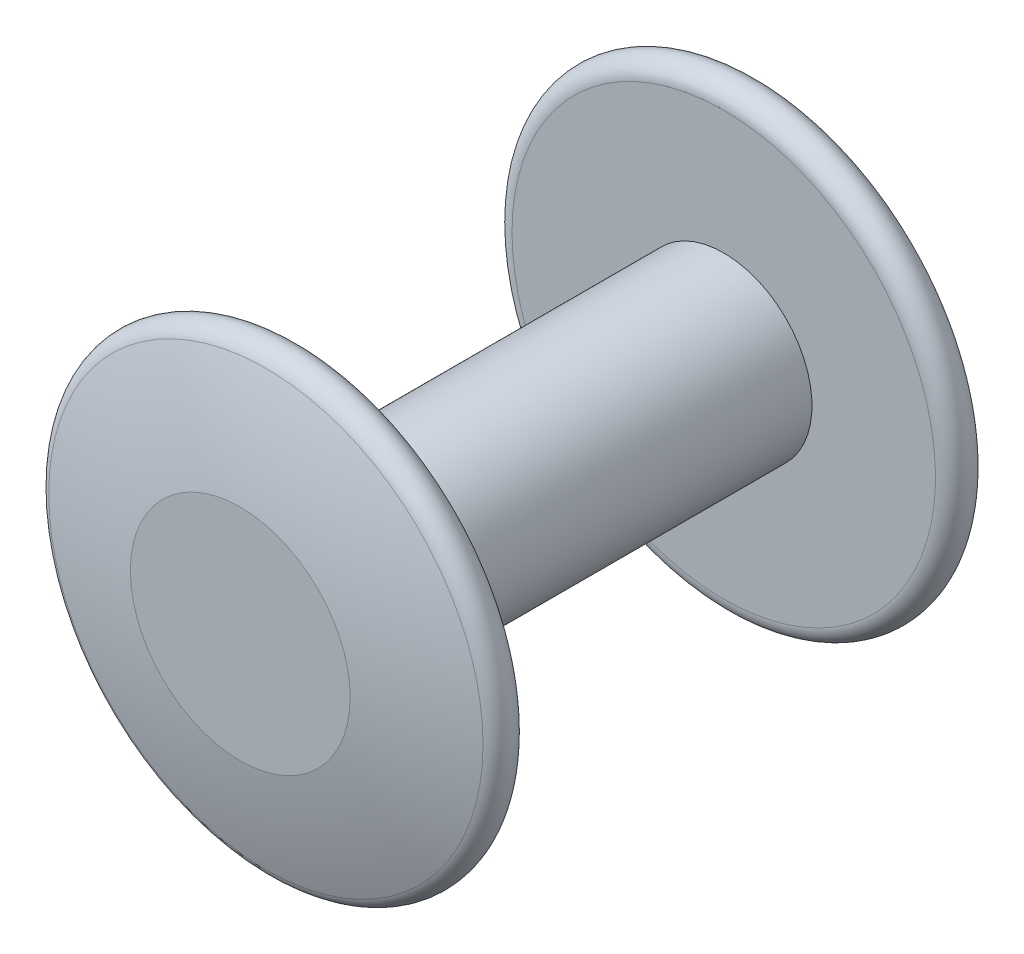
SolidWorks part; units mm, degrees
ref_plane "Front Plane" through (0, 0, 0) normal (0, 0, 1) x (1, 0, 0)
ref_plane "Top Plane" through (0, 0, 0) normal (0, 1, 0) x (1, 0, 0)
ref_plane "Right Plane" through (0, 0, 0) normal (1, 0, 0) x (0, 0, -1)
ref_plane "Plane1" through (0, 0, 0) normal (0, -1, 0) x (1, 0, 0)
sketch "Sketch1" plane through (0, 0, 0) normal (0, -1, 0) x (1, 0, 0)
  line L0 (3.1149, 7.702) -> (0, 7.702)
  line L1 (0, 7.702) -> (0, -7.702)
  line L2 (0, -7.702) -> (3.1149, -7.702)
  line L3 (6, -6) -> (2.5, -6)
  line L4 (2.5, -6) -> (2.5, 6)
  line L5 (2.5, 6) -> (6, 6)
  line L6 (0, 7.702) -> (0, -7.702) construction
  arc A0 (3.1149, -7.702) -> (6.1538, -6.9757) centre (0, 12.054) ccw
  arc A1 (6.1538, -6.9757) -> (6, -6) centre (6, -6.5) ccw
  arc A2 (6, 6) -> (6.1538, 6.9757) centre (6, 6.5) ccw
  arc A3 (6.1538, 6.9757) -> (3.1149, 7.702) centre (0, -12.054) ccw
revolve "Revolve1" add sketch "Sketch1" angle 360 about L6
